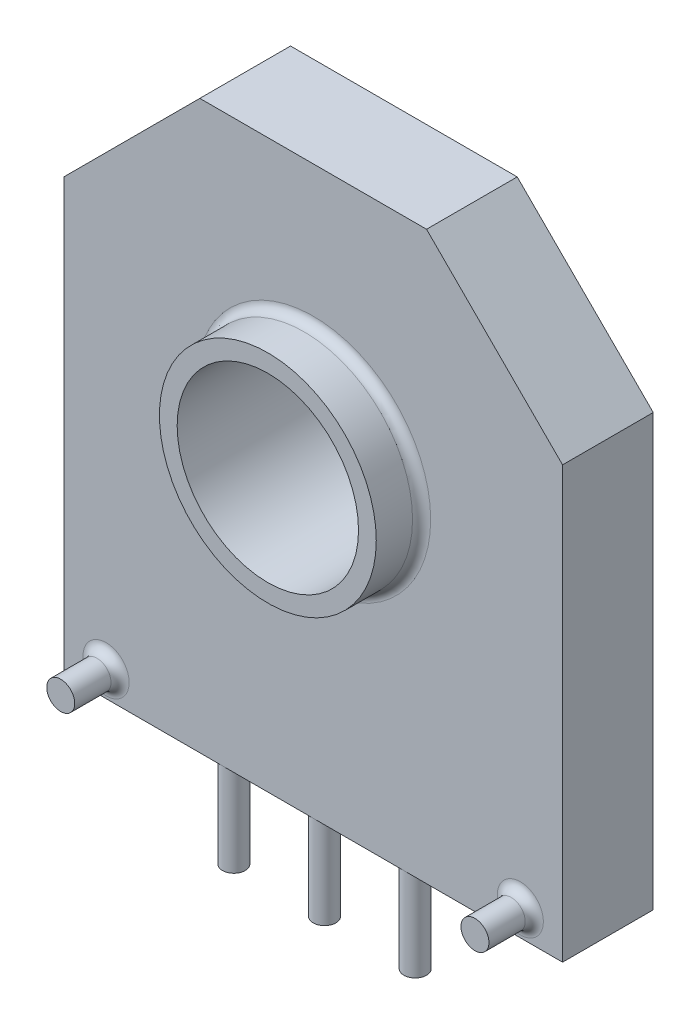
SolidWorks part; units mm, degrees
ref_plane "Front Plane" through (0, 0, 0) normal (0, 0, 1) x (1, 0, 0)
ref_plane "Top Plane" through (0, 0, 0) normal (0, 1, 0) x (1, 0, 0)
ref_plane "Right Plane" through (0, 0, 0) normal (1, 0, 0) x (0, 0, -1)
sketch "Sketch1" plane through (0, 0, 0) normal (0, 0, 1) x (1, 0, 0)
  line L0 (0, 7.3954) -> (0, -10.0149) construction
  line L1 (-4.5894, 0) -> (4.5894, 0) construction
  line L2 (0, -7) -> (5.5, -7)
  line L5 (2.5, 5.5) -> (-2.5, 5.5)
  line L6 (-2.5, 5.5) -> (-5.5, 2.5)
  line L8 (-5.5, 2.5) -> (-5.5, -7)
  line L9 (-5.5, -7) -> (0, -7)
  line L10 (5.5, 2.5) -> (5.5, -7)
  line L12 (2.5, 5.5) -> (5.5, 2.5)
  circle A0 centre (0, 0) radius 2
  point P12 (0, 0)
  point P15 (0, 5.5)
  dimension "D1" = 4
  dimension "D2" = 7
  dimension "D3" = 135
  dimension "D4" = 5.5
  dimension "D5" = 5
  dimension "D6" = 135
  dimension "D7" = 5.5
  dimension "D9" = 5.5
extrude "Boss-Extrude1" add sketch "Sketch1" along normal blind 2
sketch "Sketch2" plane through (0, 0, 2) normal (0, 0, 1) x (1, 0, 0)
  line L0 (0, 0) -> (0, -4.3405) construction
  circle A0 centre (0, 0) radius 2
  circle A1 centre (0, 0) radius 2.3915
  circle A2 centre (-4.5678, -6.4374) radius 0.3089
  circle A3 centre (4.5678, -6.4374) radius 0.3089
extrude "Boss-Extrude2" add sketch "Sketch2" along normal blind 1
fillet "Fillet1" radius 0.2 3 edges at (4.2589, -6.4374, 2) (-4.2589, -6.4374, 2) (2.3915, 0, 2)
sketch "Sketch3" plane through (0, -7, 0) normal (0, -1, 0) x (1, 0, 0)
  line L0 (0, 2) -> (0, 1.5) construction
  line L1 (-5.5, 2) -> (5.5, 2) construction
  line L2 (0, 1.75) -> (2, 1.75) construction
  circle A0 centre (0, 1.75) radius 0.25
  circle A1 centre (2, 1.75) radius 0.25
  circle A2 centre (-2, 1.75) radius 0.25
  dimension "D1" = 0.5
  dimension "D3" = 2
  dimension "D2" = 2
extrude "Boss-Extrude3" add sketch "Sketch3" along normal blind 2
